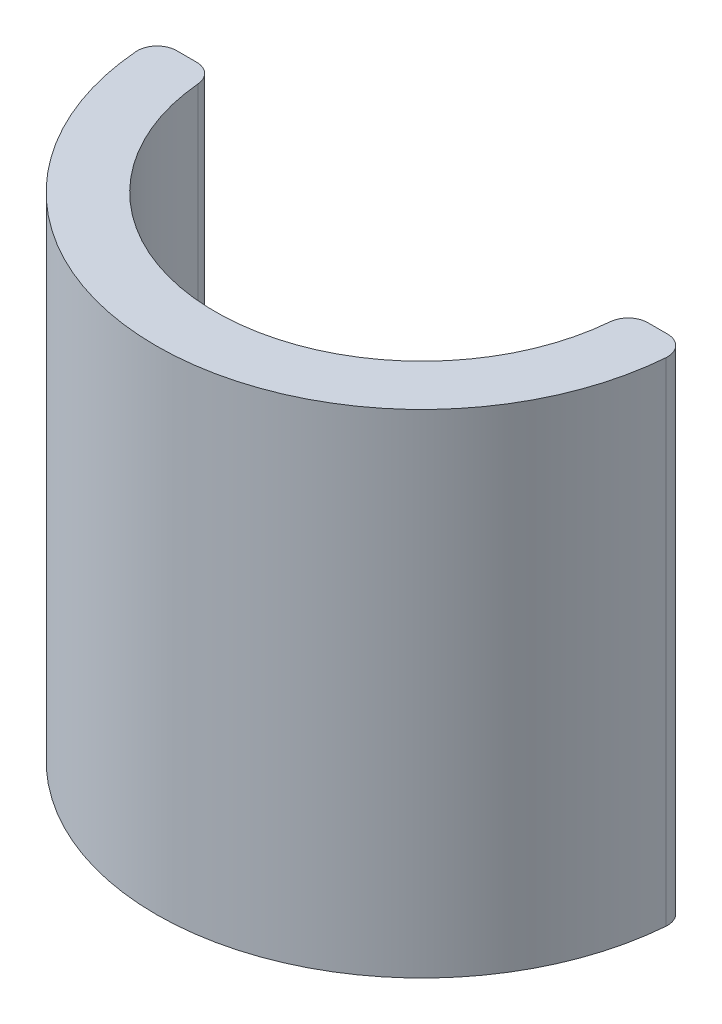
SolidWorks part; units mm, degrees
material "Бутил"
ref_plane "Спереди" through (0, 0, 0) normal (0, 0, 1) x (1, 0, 0)
ref_plane "Сверху" through (0, 0, 0) normal (0, 1, 0) x (1, 0, 0)
ref_plane "Справа" through (0, 0, 0) normal (1, 0, 0) x (0, 0, -1)
sketch "Эскиз1" plane through (0, 0, 0) normal (0, 1, 0) x (1, 0, 0)
  line L0 (-12.4599, 0) -> (-11.4564, 0)
  line L2 (13.5, 0) -> (10.5, 0)
  arc A0 (-13.4567, -1.08) -> (13.5, 0) centre (0, 0) ccw
  arc A1 (-10.4602, -0.913) -> (10.5, 0) centre (0, 0) ccw
  arc A2 (-11.4564, 0) -> (-10.4602, -0.913) centre (-11.4564, -1) cw
  circle A3 centre (0, 0) radius 10.5 construction
  circle A4 centre (0, 0) radius 13.5 construction
  arc A5 (-13.4567, -1.08) -> (-12.4599, 0) centre (-12.4599, -1) cw
  point P4 (12.9101, 3.947)
  point P9 (10.5, 0)
  point P13 (-10.5, 0)
  point P16 (-13.5, 0)
  dimension "D1" = 3
  dimension "D2" = 1
extrude "Бобышка-Вытянуть1" add sketch "Эскиз1" along normal blind 25
fillet "Скругление2" radius 1 2 edges at (13.5, 12.5, 0) (10.5, 12.5, 0)
